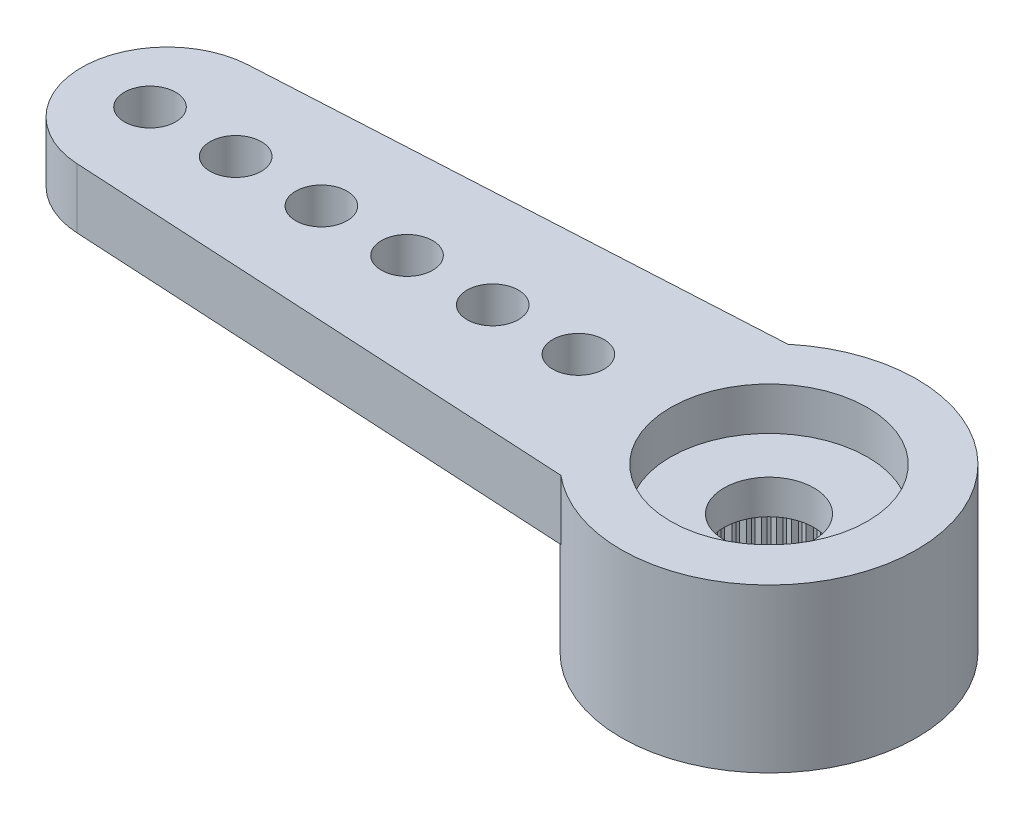
SolidWorks part; units mm, degrees
material "PVC Rígido"
ref_plane "Plano frontal" through (0, 0, 0) normal (0, 0, 1) x (1, 0, 0)
ref_plane "Plano superior" through (0, 0, 0) normal (0, 1, 0) x (1, 0, 0)
ref_plane "Plano direito" through (0, 0, 0) normal (1, 0, 0) x (0, 0, -1)
sketch "Esboço1" plane through (0, 0, 0) normal (0, 1, 0) x (1, 0, 0)
  line L0 (0, 0) -> (-14.05, 0) construction
  line L1 (-14.1591, 1.997) -> (-2.2091, 2.65)
  line L2 (-2.2091, -2.65) -> (-14.1591, -1.997)
  arc A0 (-2.2091, -2.65) -> (-2.2091, 2.65) centre (0, 0) ccw
  arc A1 (-14.1591, 1.997) -> (-14.1591, -1.997) centre (-14.05, 0) ccw
  dimension "D1" = 6.9
  dimension "D2" = 4
  dimension "D3" = 19.5
  dimension "D4" = 5.3
extrude "Ressalto-extrusão1" add sketch "Esboço1" against normal blind 1.4
sketch "Esboço2" plane through (0, -1.4, 0) normal (0, -1, 0) x (1, 0, 0)
  arc A0 (-2.2091, -2.65) -> (-2.2091, 2.65) centre (0, 0) ccw construction
  circle A1 centre (0, 0) radius 3.45
extrude "Ressalto-extrusão2" add sketch "Esboço2" along normal offset from surface (2.4 mm away) 3.8 up to face at (-7.242, 0, 0)
hole_wizard "Furo4" positions "Esboço9" profile "Esboço10" legacy end condition through all
sketch "Esboço9" plane through (0, 0, 0) normal (0, 1, 0) x (1, 0, 0)
  line L1 (-14.45, 0) -> (0, 0) construction
  arc A2 (-14.1591, 1.997) -> (-14.1591, -1.997) centre (-14.05, 0) ccw construction
  point P0 (-14.45, 0)
  point P19 (-16.05, 0)
  dimension "D1" = 1.6
sketch "Esboço10" plane through (-14.45, 0, 0) normal (1, 0, 0) x (0, 0, 1)
  line L0 (0, 0) -> (0, 3.8)
  line L1 (0, 3.8) -> (0.6, 3.8)
  line L2 (0.6, 3.8) -> (0.6, 0)
  line L3 (0.6, 0) -> (0, 0)
  line L4 (0, 110) -> (0, -10) construction
  dimension "Diameter" = 1.2
  dimension "Depth" = 3.8
pattern_linear "Padrão linear1" count 6 spacing 2 along (1, 0, 0) of "Furo4"
hole_wizard "Furo1" positions "Esboço3" profile "Esboço4" legacy
sketch "Esboço3" plane through (0, -3.8, 0) normal (0, -1, 0) x (-1, 0, 0)
  point P0 (0, 0)
sketch "Esboço4" plane through (0, -3.8, 0) normal (1, 0, 0) x (0, 0, -1)
  line L0 (0, 0) -> (0, 2)
  line L1 (0, 2) -> (2.475, 2)
  line L2 (2.475, 2) -> (2.475, 0)
  line L3 (2.475, 0) -> (0, 0)
  line L4 (0, 110) -> (0, -10) construction
  dimension "Diameter" = 4.95
  dimension "Depth" = 2
hole_wizard "Furo2" positions "Esboço5" profile "Esboço6" legacy
sketch "Esboço5" plane through (0, 0, 0) normal (0, 1, 0) x (1, 0, 0)
  point P0 (0, 0)
sketch "Esboço6" plane through (0, 0, 0) normal (1, 0, 0) x (0, 0, 1)
  line L0 (0, 0) -> (0, 1)
  line L1 (0, 1) -> (2.3, 1)
  line L2 (2.3, 1) -> (2.3, 0)
  line L3 (2.3, 0) -> (0, 0)
  line L4 (0, 110) -> (0, -10) construction
  dimension "Diameter" = 4.6
  dimension "Depth" = 1
hole_wizard "Furo3" positions "Esboço7" profile "Esboço8" legacy end condition through all
sketch "Esboço7" plane through (0, 0, 0) normal (0, 1, 0) x (1, 0, 0)
  point P0 (0, 0)
sketch "Esboço8" plane through (0, 0, 0) normal (1, 0, 0) x (0, 0, 1)
  line L0 (0, 0) -> (0, 3.8)
  line L1 (0, 3.8) -> (1.05, 3.8)
  line L2 (1.05, 3.8) -> (1.05, 0)
  line L3 (1.05, 0) -> (0, 0)
  line L4 (0, 110) -> (0, -10) construction
  dimension "Diameter" = 2.1
  dimension "Depth" = 3.8
sketch "Esboço11" plane through (0, -3.8, 0) normal (0, -1, 0) x (1, 0, 0)
  line L0 (-0.0981, 2.4731) -> (0, 2.375)
  line L1 (0, 2.375) -> (0.0981, 2.4731)
  line L2 (0, 0) -> (0, 2.475) construction
  circle A0 centre (0, 0) radius 2.375 construction
  circle A1 centre (0, 0) radius 2.475
  arc A2 (0.0981, 2.4731) -> (-0.0981, 2.4731) centre (0, 0) ccw
  dimension "D3" = 4.75
  dimension "D2" = 0.1
  dimension "D1" = 0
extrude "Ressalto-extrusão3" add sketch "Esboço11" against normal up to surface (2 mm away) up to face at (0, -1.8, 1.05)
pattern_circular "PadrãoCircular1" count 60 over 360 about axis through (0, 0, 0) along (0, 1, 0) of "Ressalto-extrusão3"
sketch "Sketch1" plane through (0, 0, 0) normal (0, 1, 0) x (1, 0, 0)
  line L0 (-14.45, 0) -> (0, 0) construction
  line L1 (-14.45, 0) -> (-12.45, 0) construction
  line L2 (0, 0) -> (-4.45, 0) construction
  line L3 (-14.45, 0) -> (-14.45, 1.9596) construction
  line L4 (-14.45, 1.9596) -> (-14.45, -1.9596) construction
  line L5 (-10.45, 0) -> (-10.45, 2.1997) construction
  line L6 (-2.2091, 2.65) -> (-14.1591, 1.997) construction
  line L7 (-10.45, 2.1997) -> (-10.45, -2.1997) construction
  line L8 (-14.1591, -1.997) -> (-2.2091, -2.65) construction
  line L9 (-2.2091, 2.65) -> (-2.2091, -2.65) construction
  line L10 (0, 0) -> (-2.2091, 0.612) construction
  arc A0 (-14.1591, 1.997) -> (-14.1591, -1.997) centre (-14.05, 0) ccw construction
sketch "Sketch2" plane through (0, 0, 0) normal (0, 1, 0) x (1, 0, 0)
  circle A0 centre (-14.45, 0) radius 0.6 construction
  circle A1 centre (-14.45, 0) radius 0.6
